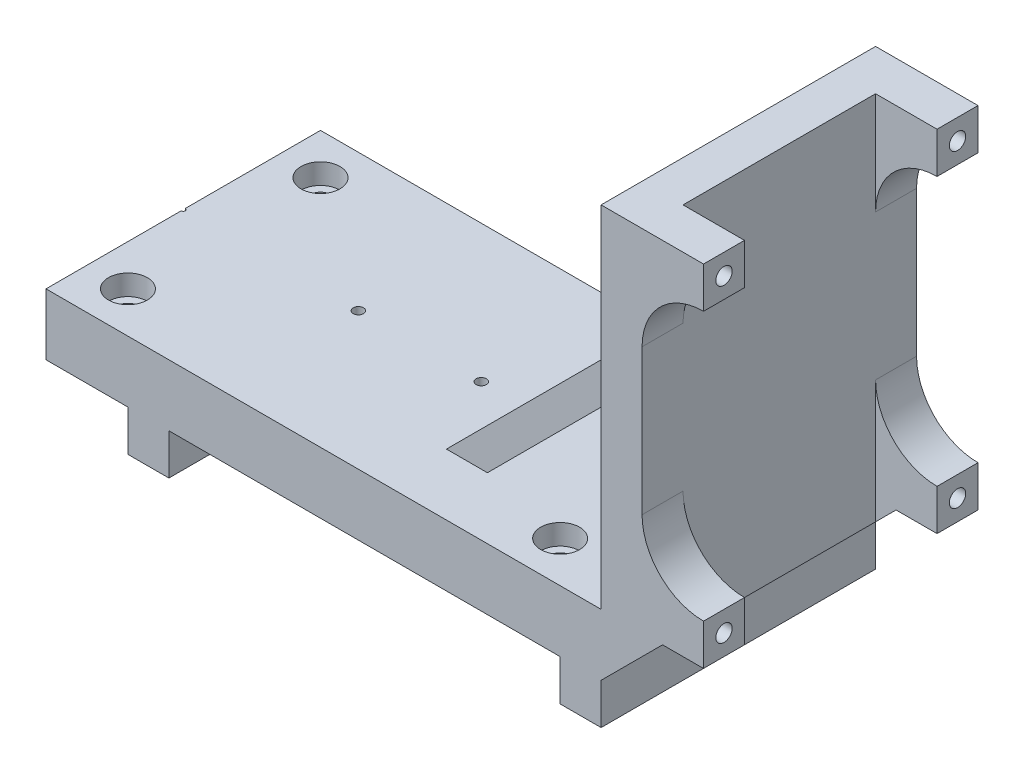
SolidWorks part; units mm, degrees
ref_plane "정면" through (0, 0, 0) normal (0, 0, 1) x (1, 0, 0)
ref_plane "윗면" through (0, 0, 0) normal (0, 1, 0) x (1, 0, 0)
ref_plane "우측면" through (0, 0, 0) normal (1, 0, 0) x (0, 0, -1)
sketch "스케치1" plane through (0, 0, 0) normal (0, 0, 1) x (1, 0, 0)
  line L0 (10, 75.5) -> (10, 60.5)
  line L1 (0, 0) -> (10, 0)
  line L2 (0, 0) -> (0, 85.5)
  line L3 (0, 85.5) -> (10, 85.5)
  line L4 (10, 0) -> (10, 85.5)
  line L5 (0, 0) -> (-85.5, 0)
  line L6 (0, 0) -> (0, -15)
  line L7 (0, -15) -> (-85.5, -15)
  line L8 (-85.5, 0) -> (-85.5, -15)
  line L9 (10, 85.5) -> (25, 85.5)
  line L10 (10, 85.5) -> (10, 75.5)
  line L11 (10, 75.5) -> (25, 75.5)
  line L12 (25, 85.5) -> (25, 75.5)
  line L13 (10, 0) -> (25, 0)
  line L14 (10, 0) -> (10, 10)
  line L15 (10, 10) -> (25, 10)
  line L16 (25, 0) -> (25, 10)
  line L17 (0, -15) -> (-10, -15)
  line L18 (0, -15) -> (0, -25)
  line L19 (0, -25) -> (-10, -25)
  line L20 (-10, -15) -> (-10, -25)
  line L21 (-85.5, -15) -> (-75.5, -15)
  line L22 (-85.5, -15) -> (-85.5, -25)
  line L25 (10, 60.5) -> (25, 75.5)
  line L26 (10, 10) -> (10, 25)
  line L27 (10, 25) -> (25, 10)
  line L28 (-10, -15) -> (-30, -15)
  line L29 (15, 0) -> (0, -15)
  line L30 (-75.5, -15) -> (-60.5, -15)
  line L31 (-10, -15) -> (-75.5, -15)
  line L32 (0, 0) -> (0, 42.75)
  line L33 (0, 42.75) -> (-42.75, 0)
  line L34 (-42.75, 0) -> (-52.75, 0)
  line L35 (-52.75, 0) -> (0, 52.75)
  line L36 (0, 52.75) -> (0, 42.75)
  line L37 (10, 0) -> (15, 0)
  line L38 (-85.5, 0) -> (-115.5, 0)
  line L39 (-85.5, 0) -> (-85.5, -25)
  line L40 (-85.5, -25) -> (-115.5, -25)
  line L41 (-115.5, 0) -> (-115.5, -25)
  line L46 (-115.5, 0) -> (-135.5, 0)
  line L47 (-115.5, 0) -> (-115.5, -15)
  line L48 (-115.5, -15) -> (-135.5, -15)
  line L49 (-135.5, 0) -> (-135.5, -15)
  line L55 (0, -20) -> (0, -15)
  line L56 (-10, -15) -> (-10, -25)
  arc A0 (10, 60.5) -> (25, 75.5) centre (25, 60.5) cw
  arc A1 (10, 25) -> (25, 10) centre (25, 25) ccw
  point P18 (0, 0)
  dimension "D1" = 85.5
  dimension "D2" = 10
  dimension "D3" = 85.5
  dimension "D4" = 15
  dimension "D5" = 10
  dimension "D6" = 10
  dimension "D7" = 10
  dimension "D8" = 10
  dimension "D9" = 15
  dimension "D10" = 15
  dimension "D11" = 10
  dimension "D13" = 15
  dimension "D14" = 15
  dimension "D17" = 10
  dimension "D18" = 30
  dimension "D19" = 20
  dimension "D20" = 15
  dimension "D21" = 5
extrude "보스-돌출2" add sketch "스케치1" along normal blind 67
sketch "스케치2" plane through (0, 0, 67) normal (0, 0, 1) x (1, 0, 0)
  line L0 (0, 52.75) -> (0, 42.75)
  line L1 (0, 42.75) -> (-42.75, 0)
  line L2 (-42.75, 0) -> (-52.75, 0)
  line L3 (-52.75, 0) -> (0, 52.75)
extrude "컷-돌출5" cut sketch "스케치2" against normal blind 15
sketch "스케치3" plane through (0, 0, 0) normal (0, 0, -1) x (-1, 0, 0)
  line L0 (0, 52.75) -> (0, 42.75)
  line L1 (0, 42.75) -> (42.75, 0)
  line L2 (42.75, 0) -> (52.75, 0)
  line L3 (52.75, 0) -> (0, 52.75)
extrude "컷-돌출6" cut sketch "스케치3" against normal blind 15
sketch "스케치4" plane through (0, 85.5, 0) normal (0, 1, 0) x (1, 0, 0)
  line L0 (0, 0) -> (10, 0)
  line L1 (0, 0) -> (25, 0) construction
  line L2 (10, 0) -> (10, -10)
  line L3 (25, -67) -> (25, 0) construction
  line L4 (10, -10) -> (25, -10)
  line L5 (10, -10) -> (10, -57)
  line L6 (10, -57) -> (25, -57)
  line L7 (25, -10) -> (25, -57)
  line L8 (25, -57) -> (25, -67)
  line M7 (25, -67) -> (25, 0)
  dimension "D1" = 10
  dimension "D2" = 10
  dimension "D3" = 10
extrude "컷-돌출7" cut sketch "스케치4" against normal blind 100 contours L5 L6 L4 M7
sketch "스케치5" plane through (0, 0, 0) normal (0, 1, 0) x (1, 0, 0)
  line L0 (-135.5, 0) -> (-135.5, -33.5)
  line L1 (-135.5, -67) -> (-135.5, 0) construction
  line L2 (-135.5, -33) -> (-135.5, -34)
  arc A0 (-135.5, -33) -> (-135.5, -34) centre (-135.5, -33.5) cw
  line M2 (-135.5, 0) -> (-135.5, -67)
  dimension "D1" = 0.5
extrude "컷-돌출8" cut sketch "스케치5" against normal blind 100 contours A0 L0 M2
sketch "스케치8" plane through (25, 0, 0) normal (1, 0, 0) x (0, 0, -1)
  line L0 (-67, 85.5) -> (-67, 80.5)
  line L1 (-67, 85.5) -> (-67, 75.5) construction
  line L2 (-67, 80.5) -> (-57, 80.5)
  line L3 (-57, 75.5) -> (-57, 85.5) construction
  circle A0 centre (-62, 80.5) radius 2
  dimension "D1" = 4
extrude "컷-돌출11" cut sketch "스케치8" against normal blind 25 contours L2 A0
sketch "스케치10" plane through (25, 0, 0) normal (1, 0, 0) x (0, 0, -1)
  line L0 (-10, 85.5) -> (-10, 80.5)
  line L1 (-10, 75.5) -> (-10, 85.5) construction
  line L2 (-10, 80.5) -> (0, 80.5)
  line L3 (0, 85.5) -> (0, 75.5) construction
  circle A0 centre (-5, 80.5) radius 2
  dimension "D1" = 4
extrude "컷-돌출12" cut sketch "스케치10" against normal blind 25 contours L2 A0 | L2 A0
sketch "스케치11" plane through (25, 0, 0) normal (1, 0, 0) x (0, 0, -1)
  line L0 (-57, 10) -> (-57, 5)
  line L1 (-57, 0) -> (-57, 10) construction
  line L2 (-57, 5) -> (-67, 5)
  line L3 (-67, 0) -> (-67, 10) construction
  circle A0 centre (-62, 5) radius 2
  dimension "D1" = 4
extrude "컷-돌출13" cut sketch "스케치11" against normal blind 25 contours L2 A0 | L2 A0
sketch "스케치12" plane through (25, 0, 0) normal (1, 0, 0) x (0, 0, -1)
  line L0 (0, 10) -> (0, 5)
  line L1 (0, 0) -> (0, 10) construction
  line L2 (0, 5) -> (-10, 5)
  line L3 (-10, 0) -> (-10, 10) construction
  circle A0 centre (-5, 5) radius 2
  dimension "D1" = 4
extrude "컷-돌출14" cut sketch "스케치12" against normal blind 25 contours L2 A0 | L2 A0
sketch "스케치17" plane through (0, 0, 0) normal (0, 1, 0) x (1, 0, 0)
  line L0 (-135.5, 0) -> (-125.5, 0)
  line L1 (0, 0) -> (-135.5, 0) construction
  line L2 (-125.5, 0) -> (-125.5, -67)
  line L3 (0, -67) -> (-135.5, -67) construction
  line L4 (-125.5, -67) -> (-125.5, -57)
  line L5 (-125.5, 0) -> (-125.5, -10)
  line L6 (0, 0) -> (-20, 0)
  line L7 (-20, 0) -> (-20, -67)
  line L8 (-20, -67) -> (-20, -57)
  line L9 (-20, -57) -> (-20, -10)
  dimension "D1" = 10
  dimension "D2" = 10
  dimension "D3" = 10
  dimension "D4" = 20
hole_wizard "M5 소켓 머리 캡 나사용 카운터보어1" positions "스케치20" profile "스케치21" counterbore size "M5" standard "KS" end condition through all
sketch "스케치20" plane through (0, 0, 0) normal (0, 1, 0) x (1, 0, 0)
  point P0 (-125.5, -10)
  point P3 (-125.5, -57)
  point P6 (-20, -10)
  point P9 (-20, -57)
sketch "스케치21" plane through (-125.5, 0, 10) normal (1, 0, 0) x (0, 0, 1)
  line L0 (0, 0) -> (0, 25)
  line L1 (0, 25) -> (2.75, 25)
  line L3 (2.75, 25) -> (2.75, 5)
  line L4 (2.75, 5) -> (4.75, 5)
  line L5 (4.75, 5) -> (4.75, 0)
  line L7 (4.75, 0) -> (0, 0)
  line L11 (0, -6.35) -> (0, 107.95) construction
  dimension "관통 구멍 지름" = 5.5
  dimension "관통 구멍 깊이" = 25
  dimension "카운터보어 지름" = 9.5
  dimension "카운터보어 깊이" = 5
sketch "스케치24" plane through (0, 0, 0) normal (0, 1, 0) x (1, 0, 0)
  line L0 (-52.75, -52) -> (-52.75, -15) construction
  line L1 (-52.75, -33.5) -> (-92.75, -33.5)
  line L2 (-92.75, -33.5) -> (-62.75, -33.5)
  circle A0 centre (-62.75, -33.5) radius 1.25
  circle A1 centre (-92.75, -33.5) radius 1.25
  dimension "D3" = 2.5
  dimension "D4" = 2.5
  dimension "D1" = 40
  dimension "D2" = 30
extrude "컷-돌출15" cut sketch "스케치24" against normal blind 50
sketch "스케치25" plane through (0, 0, 0) normal (0, 0, -1) x (-1, 0, 0)
  line L1 (85.5, -25) -> (105.5, -25)
  line L2 (85.5, -25) -> (85.5, -15)
  line L3 (85.5, -15) -> (105.5, -15)
  line L4 (105.5, -25) -> (105.5, -15)
  dimension "D1" = 20
  dimension "D2" = 10
extrude "컷-돌출16" cut sketch "스케치25" against normal blind 100
